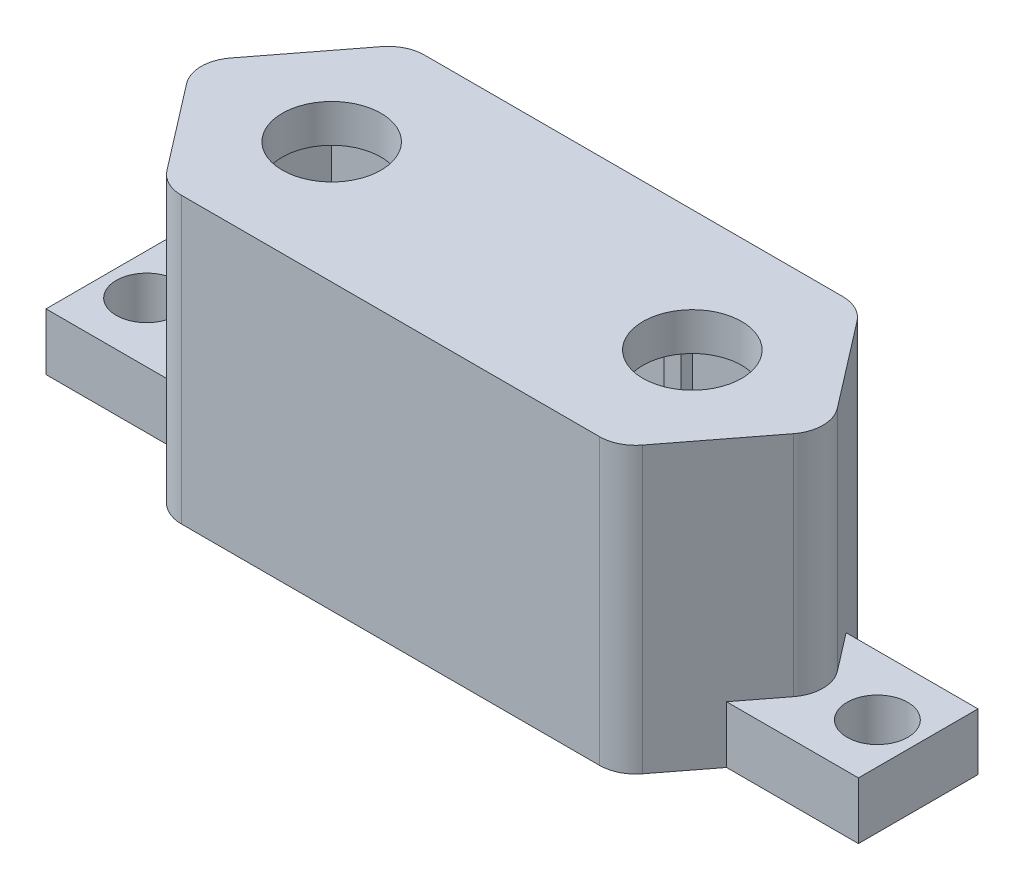
SolidWorks part; units mm, degrees
ref_plane "Front Plane" through (0, 0, 0) normal (0, 0, 1) x (1, 0, 0)
ref_plane "Top Plane" through (0, 0, 0) normal (0, 1, 0) x (1, 0, 0)
ref_plane "Right Plane" through (0, 0, 0) normal (1, 0, 0) x (0, 0, -1)
sketch "Sketch1" plane through (0, 0, 0) normal (0, 1, 0) x (1, 0, 0)
  line L0 (0, 0) -> (17, 0) construction
  line L1 (12, -6.5) -> (-12, -6.5)
  line L2 (12, -6.5) -> (12, 6.5)
  line L3 (12, 6.5) -> (-12, 6.5)
  line L4 (-12, -6.5) -> (-12, 6.5)
  line L5 (12, -6.5) -> (-12, 6.5) construction
  line L6 (12, 6.5) -> (-12, -6.5) construction
  line L7 (12, 6.5) -> (17, 0)
  line L8 (17, 0) -> (12, -6.5)
  line L9 (0, 6.5) -> (0, -6.5) construction
  line L10 (-17, 0) -> (-12, -6.5)
  line L11 (-12, 6.5) -> (-17, 0)
  point P0 (0, 0)
  dimension "D1" = 24
  dimension "D2" = 13
  dimension "D3" = 17
extrude "Boss-Extrude1" add sketch "Sketch1" along normal blind 15 contours L4 L11 L10 | L4 L1 L2 L3 | L8 L7 L2
sketch "Sketch2" plane through (0, 0, 0) normal (0, -1, 0) x (1, 0, 0)
  line L5 (-14.4767, 0) -> (-11.0152, -4.5)
  line L6 (12, -6.5) -> (-12, -6.5) construction
  line L7 (-14.4767, 0) -> (-11.0152, 4.5)
  line L8 (-12, -6.5) -> (-17, 0) construction
  line L9 (0, 6.5) -> (0, -6.5) construction
  line L10 (-17, 0) -> (-12, 6.5) construction
  line L11 (14.4767, 0) -> (11.0152, -4.5)
  line L12 (12, 6.5) -> (-12, 6.5) construction
  line L14 (14.4767, 0) -> (11.0152, 4.5)
  line L15 (-11.0152, 4.5) -> (13.5385, 4.5)
  line L16 (17, 0) -> (12, 6.5) construction
  line L17 (-11.0152, -4.5) -> (11.0152, -4.5)
  dimension "D1" = 2
  dimension "D2" = 2
  dimension "D3" = 2
  dimension "D4" = 2
extrude "Cut-Extrude1" cut sketch "Sketch2" against normal blind 13 contours L9 L15 L7 L5 L17 | L15 L9 L17 L11 L14
sketch "Sketch3" plane through (0, 15, 0) normal (0, 1, 0) x (1, 0, 0)
  line L0 (0, 6.5) -> (0, -6.5) construction
  line L1 (12, 6.5) -> (-12, 6.5) construction
  line L2 (12, -6.5) -> (-12, -6.5) construction
  line L3 (-17, 0) -> (17, 0) construction
  circle A0 centre (-9.5, 0) radius 2.6
  circle A1 centre (9.5, 0) radius 2.6
  dimension "D1" = 5.2
  dimension "D2" = 19
  dimension "D3" = 9.5
extrude "Cut-Extrude2" cut sketch "Sketch3" against normal blind 2
sketch "Sketch4" plane through (0, 13, 0) normal (0, -1, 0) x (1, 0, 0)
  line L0 (-6.4, 2.5) -> (-5.5, 2.5)
  line L1 (-6.4, -3.1) -> (-12.0921, -3.1)
  line L2 (-6.4, -3.1) -> (-6.4, -2.5)
  line L3 (-6.4, 3.1) -> (-12.0823, 3.1)
  line L4 (-12.6, -2.4398) -> (-12.6, 2.4398)
  line L5 (-6.4, -3.1) -> (-12.6, 3.1) construction
  line L6 (-6.4, 3.1) -> (-12.6, -3.1) construction
  line L7 (-5.5, -4) -> (-13.5, -4)
  line L8 (-5.5, -4) -> (-5.5, -2.5)
  line L9 (-5.5, 4) -> (-13.5, 4)
  line L10 (-13.5, -4) -> (-13.5, 4)
  line L11 (-5.5, -4) -> (-13.5, 4) construction
  line L12 (-5.5, 4) -> (-13.5, -4) construction
  line L13 (-6.4, -2.5) -> (-5.5, -2.5)
  line L14 (-6.4, 0) -> (-5.5, 0) construction
  line L15 (-5.5, 2.5) -> (-5.5, 4)
  line L16 (-6.4, 2.5) -> (-6.4, 3.1)
  line L17 (-9.5, 0) -> (-5.5, 0) construction
  line L18 (0, 4.5) -> (0, -4.5) construction
  line L19 (-11.0152, 4.5) -> (11.0152, 4.5) construction
  line L20 (-11.0152, -4.5) -> (11.0152, -4.5) construction
  line L21 (6.4, 2.5) -> (6.4, 3.1)
  line L22 (6.4, 2.5) -> (5.5, 2.5)
  line L23 (5.5, 2.5) -> (5.5, 4)
  line L24 (5.5, 4) -> (13.5, 4)
  line L25 (13.5, -4) -> (13.5, 4)
  line L26 (5.5, -4) -> (13.5, -4)
  line L27 (5.5, -4) -> (5.5, -2.5)
  line L28 (6.4, -2.5) -> (5.5, -2.5)
  line L29 (6.4, -3.1) -> (6.4, -2.5)
  line L30 (6.4, -3.1) -> (12.0921, -3.1)
  line L31 (12.6, -2.4398) -> (12.6, 2.4398)
  line L32 (6.4, 3.1) -> (12.0823, 3.1)
  line L33 (-12.0823, 3.1) -> (-12.6, 2.4398)
  line L34 (-14.4767, 0) -> (-11.0152, 4.5) construction
  line L35 (-12.6, -2.4398) -> (-12.0921, -3.1)
  line L36 (-14.4767, 0) -> (-11.0152, -4.5) construction
  line L37 (12.6, -2.4398) -> (12.0921, -3.1)
  line L38 (12.0823, 3.1) -> (12.6, 2.4398)
  line L39 (-9.5, 0) -> (-9.5, 3.1) construction
  point P0 (-9.5, 0)
  point P6 (-9.5, 0)
  dimension "D1" = 6.2
  dimension "D2" = 8
  dimension "D3" = 5
  dimension "D4" = 2.5
  dimension "D5" = 0.9
  dimension "D6" = 0.9
  dimension "D7" = 1.5
  dimension "D8" = 0.9
extrude "Cut-Extrude3" cut sketch "Sketch4" along normal blind 13
sketch "Sketch5" plane through (0, 13, 0) normal (0, -1, 0) x (1, 0, 0)
  line L0 (0, 4.5) -> (0, -4.5) construction
  line L1 (-11.0152, 4.5) -> (11.0152, 4.5) construction
  line L2 (-11.0152, -4.5) -> (11.0152, -4.5) construction
  line L3 (-9.5, 0) -> (0, 0) construction
  line L4 (-6.4, -3.1) -> (-12.6, -3.1)
  line L5 (-6.4, -3.1) -> (-6.4, -2.5)
  line L6 (-6.4, 3.1) -> (-12.6, 3.1)
  line L7 (-12.6, -3.1) -> (-12.6, 3.1)
  line L8 (-6.4, -3.1) -> (-12.6, 3.1) construction
  line L9 (-6.4, 3.1) -> (-12.6, -3.1) construction
  line L10 (-13.5, 4) -> (-5.5, 4)
  line L11 (-13.5, 4) -> (-13.5, -4)
  line L12 (-13.5, -4) -> (-5.5, -4)
  line L13 (-5.5, 4) -> (-5.5, 2.5)
  line L14 (-13.5, 4) -> (-5.5, -4) construction
  line L15 (-13.5, -4) -> (-5.5, 4) construction
  line L16 (-6.4, 2.5) -> (-5.5, 2.5)
  line L17 (-6.4, -2.5) -> (-5.5, -2.5)
  line L18 (12.6, -3.1) -> (12.6, 3.1)
  line L19 (13.5, 4) -> (13.5, -4)
  line L20 (13.5, -4) -> (5.5, -4)
  line L21 (6.4, -3.1) -> (12.6, -3.1)
  line L22 (6.4, -2.5) -> (5.5, -2.5)
  line L23 (6.4, 2.5) -> (5.5, 2.5)
  line L24 (6.4, -3.1) -> (6.4, -2.5)
  line L25 (5.5, 4) -> (5.5, 2.5)
  line L26 (13.5, 4) -> (5.5, 4)
  line L27 (6.4, 3.1) -> (12.6, 3.1)
  line L28 (-5.5, -2.5) -> (-5.5, -4)
  line L29 (-6.4, 2.5) -> (-6.4, 3.1)
  line L30 (5.5, -2.5) -> (5.5, -4)
  line L31 (6.4, 2.5) -> (6.4, 3.1)
  point P6 (-9.5, 0)
  point P12 (-9.5, 0)
  dimension "D1" = 6.2
  dimension "D2" = 8
  dimension "D3" = 2.5
  dimension "D4" = 5
extrude "Boss-Extrude3" add sketch "Sketch5" along normal blind 8
ref_plane "Plane1" through (0, 0, 0) normal (0, 1, 0) x (1, 0, 0)
sketch "Sketch6" plane through (0, 0, 0) normal (0, 1, 0) x (1, 0, 0)
  line L0 (12, 6.5) -> (17, 0) construction
  line L1 (17, 0) -> (12, -6.5) construction
  line L2 (12, -6.5) -> (-12, -6.5) construction
  line L3 (-17, 0) -> (-12, -6.5) construction
  line L4 (-12, 6.5) -> (-17, 0) construction
  line L5 (12, 6.5) -> (-12, 6.5) construction
  line L6 (12, 6.5) -> (17, 0)
  line L7 (17, 0) -> (12, -6.5)
  line L8 (12, -6.5) -> (-12, -6.5)
  line L9 (-17, 0) -> (-12, -6.5)
  line L10 (-12, 6.5) -> (-17, 0)
  line L11 (12, 6.5) -> (-12, 6.5)
  line L12 (-14.5, 3.25) -> (-21.5, 3.25)
  line L13 (-21.5, 3.25) -> (-21.5, -3.25)
  line L14 (-21.5, -3.25) -> (-14.5, -3.25)
  line L15 (0, 6.5) -> (0, -6.5) construction
  line L16 (-17, 0) -> (-21.5, 0) construction
  line L17 (21.5, -3.25) -> (14.5, -3.25)
  line L18 (21.5, 3.25) -> (21.5, -3.25)
  line L19 (14.5, 3.25) -> (21.5, 3.25)
  circle A0 centre (-19.25, 0) radius 1.6
  circle A1 centre (19.25, 0) radius 1.6
  dimension "D2" = 3.2
  dimension "D1" = 7
extrude "Boss-Extrude4" add sketch "Sketch6" along normal blind 3 contours L19 L6 L7 L17 L18 A1 | L13 L14 L9 L10 L12 A0
fillet "Fillet1" radius 2 6 edges at (-12, 7.5, -6.5) (-17, 9, 0) (-12, 7.5, 6.5) (12, 7.5, 6.5) (12, 7.5, -6.5) (17, 9, 0)
sketch "Sketch8" plane through (0, 0, 0) normal (0, -1, 0) x (1, 0, 0)
  line L0 (-14.5, -3.25) -> (-21.5, -3.25) construction
  line L1 (-12.6004, -5.7194) -> (-14.5, -3.25) construction
  line L2 (11.0152, -6.5) -> (-11.0152, -6.5) construction
  line L3 (12.6004, -5.7194) -> (14.5, -3.25) construction
  line L4 (14.5, -3.25) -> (21.5, -3.25) construction
  line L5 (21.5, -3.25) -> (21.5, 3.25) construction
  line L6 (21.5, 3.25) -> (14.5, 3.25) construction
  line L7 (14.5, 3.25) -> (12.6004, 5.7194) construction
  line L8 (11.0152, 6.5) -> (-11.0152, 6.5) construction
  line L9 (-14.5, 3.25) -> (-12.6004, 5.7194) construction
  line L10 (-21.5, 3.25) -> (-14.5, 3.25) construction
  line L11 (-21.5, -3.25) -> (-21.5, 3.25) construction
  line L12 (-14.5, -3.25) -> (-21.5, -3.25)
  line L13 (-12.6004, -5.7194) -> (-14.5, -3.25)
  line L14 (11.0152, -6.5) -> (-11.0152, -6.5)
  line L15 (12.6004, -5.7194) -> (14.5, -3.25)
  line L16 (14.5, -3.25) -> (21.5, -3.25)
  line L17 (21.5, -3.25) -> (21.5, 3.25)
  line L18 (21.5, 3.25) -> (14.5, 3.25)
  line L19 (14.5, 3.25) -> (12.6004, 5.7194)
  line L20 (11.0152, 6.5) -> (-11.0152, 6.5)
  line L21 (-14.5, 3.25) -> (-12.6004, 5.7194)
  line L22 (-21.5, 3.25) -> (-14.5, 3.25)
  line L23 (-21.5, -3.25) -> (-21.5, 3.25)
  line L24 (-14.4508, -3.15) -> (-21.4, -3.15)
  line L25 (-21.4, -3.15) -> (-21.4, 3.15)
  line L26 (-21.4, 3.15) -> (-14.4508, 3.15)
  line L27 (-14.4508, 3.15) -> (-12.5212, 5.6585)
  line L28 (11.0152, 6.4) -> (-11.0152, 6.4)
  line L29 (14.4508, 3.15) -> (12.5212, 5.6585)
  line L30 (21.4, 3.15) -> (14.4508, 3.15)
  line L31 (21.4, -3.15) -> (21.4, 3.15)
  line L32 (14.4508, -3.15) -> (21.4, -3.15)
  line L33 (12.5212, -5.6585) -> (14.4508, -3.15)
  line L34 (11.0152, -6.4) -> (-11.0152, -6.4)
  line L35 (-12.5212, -5.6585) -> (-14.4508, -3.15)
  arc A0 (-12.6004, -5.7194) -> (-11.0152, -6.5) centre (-11.0152, -4.5) ccw construction
  arc A1 (11.0152, -6.5) -> (12.6004, -5.7194) centre (11.0152, -4.5) ccw construction
  arc A2 (12.6004, 5.7194) -> (11.0152, 6.5) centre (11.0152, 4.5) ccw construction
  arc A3 (-11.0152, 6.5) -> (-12.6004, 5.7194) centre (-11.0152, 4.5) ccw construction
  arc A4 (-12.6004, -5.7194) -> (-11.0152, -6.5) centre (-11.0152, -4.5) ccw
  arc A5 (11.0152, -6.5) -> (12.6004, -5.7194) centre (11.0152, -4.5) ccw
  arc A6 (12.6004, 5.7194) -> (11.0152, 6.5) centre (11.0152, 4.5) ccw
  arc A7 (-11.0152, 6.5) -> (-12.6004, 5.7194) centre (-11.0152, 4.5) ccw
  arc A8 (-11.0152, 6.4) -> (-12.5212, 5.6585) centre (-11.0152, 4.5) ccw
  arc A9 (12.5212, 5.6585) -> (11.0152, 6.4) centre (11.0152, 4.5) ccw
  arc A10 (11.0152, -6.4) -> (12.5212, -5.6585) centre (11.0152, -4.5) ccw
  arc A11 (-12.5212, -5.6585) -> (-11.0152, -6.4) centre (-11.0152, -4.5) ccw
  dimension "D1" = 0.1
extrude "Cut-Extrude8" cut sketch "Sketch8" against normal through all
sketch "Sketch9" plane through (0, 15, 0) normal (0, 1, 0) x (1, 0, 0)
  line L0 (14.5769, -3.15) -> (14.4508, -3.15) construction
  line L1 (14.4508, 3.15) -> (14.5769, 3.15) construction
  line L2 (-14.4508, -3.15) -> (-14.5769, -3.15) construction
  line L3 (-14.5769, 3.15) -> (-14.4508, 3.15) construction
  line L4 (16.062, -1.2194) -> (14.5769, -3.15) construction
  line L5 (14.5769, 3.15) -> (16.062, 1.2194) construction
  line L6 (-16.062, -1.2194) -> (-14.5769, -3.15) construction
  line L7 (-14.5769, 3.15) -> (-16.062, 1.2194) construction
  line L8 (14.5769, -3.15) -> (14.4508, -3.15)
  line L9 (14.4508, 3.15) -> (14.5769, 3.15)
  line L10 (-14.4508, -3.15) -> (-14.5769, -3.15)
  line L11 (-14.5769, 3.15) -> (-14.4508, 3.15)
  line L12 (16.062, -1.2194) -> (14.5769, -3.15)
  line L13 (14.5769, 3.15) -> (16.062, 1.2194)
  line L14 (-16.062, -1.2194) -> (-14.5769, -3.15)
  line L15 (-14.5769, 3.15) -> (-16.062, 1.2194)
  line L16 (14.4508, 3.15) -> (14.5277, 3.05)
  line L17 (14.5277, 3.05) -> (15.9827, 1.1585)
  line L18 (15.9827, -1.1585) -> (14.5277, -3.05)
  line L19 (14.5277, -3.05) -> (14.4508, -3.15)
  line L20 (-14.5277, -3.05) -> (-14.4508, -3.15)
  line L21 (-14.5277, 3.05) -> (-15.9827, 1.1585)
  line L22 (-15.9827, -1.1585) -> (-14.5277, -3.05)
  line L24 (14.4508, 3.05) -> (14.5277, 3.05) construction
  line L25 (-14.5277, 3.05) -> (-14.4508, 3.15)
  line L26 (14.5277, -3.05) -> (14.4508, -3.05) construction
  line L31 (-14.5277, 3.05) -> (-14.4508, 3.05) construction
  line L32 (-14.4508, -3.05) -> (-14.5277, -3.05) construction
  arc A0 (16.062, -1.2194) -> (16.062, 1.2194) centre (14.4767, 0) ccw construction
  arc A1 (-16.062, 1.2194) -> (-16.062, -1.2194) centre (-14.4767, 0) ccw construction
  arc A2 (16.062, -1.2194) -> (16.062, 1.2194) centre (14.4767, 0) ccw
  arc A3 (-16.062, 1.2194) -> (-16.062, -1.2194) centre (-14.4767, 0) ccw
  arc A4 (15.9827, -1.1585) -> (15.9827, 1.1585) centre (14.4767, 0) ccw
  arc A5 (-15.9827, 1.1585) -> (-15.9827, -1.1585) centre (-14.4767, 0) ccw
  point P9 (14.5138, 3.15)
  dimension "D2" = 0.1
  dimension "D1" = 0.1
extrude "Cut-Extrude9" cut sketch "Sketch9" against normal up to surface (12 mm away) up to face at (-19.25, 3, 1.6)
